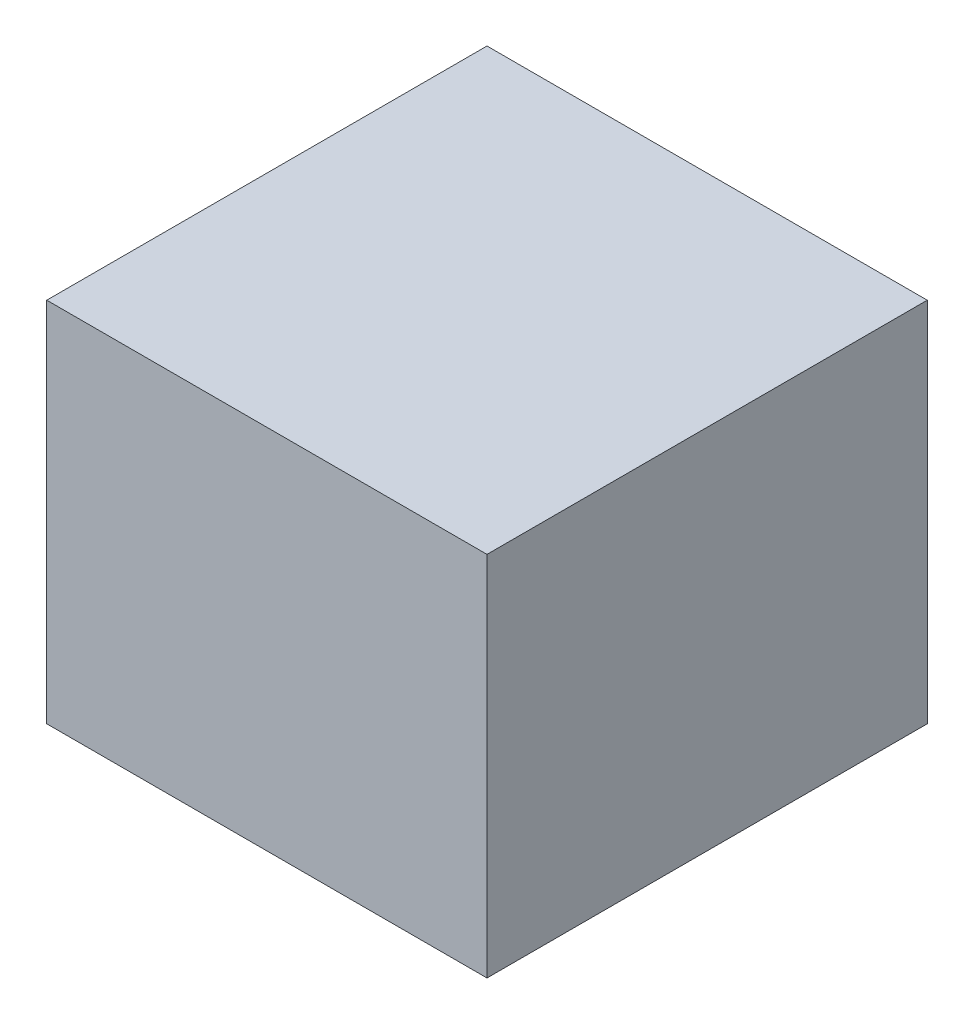
SolidWorks part; units mm, degrees
ref_plane "Front Plane" through (0, 0, 0) normal (0, 0, 1) x (1, 0, 0)
ref_plane "Top Plane" through (0, 0, 0) normal (0, 1, 0) x (1, 0, 0)
ref_plane "Right Plane" through (0, 0, 0) normal (1, 0, 0) x (0, 0, -1)
sketch "Sketch1" plane through (0, 0, 0) normal (0, 0, 1) x (1, 0, 0)
  line L1 (-31.034, 220.9056) -> (268.966, 220.9056)
  line L2 (-31.034, 220.9056) -> (-31.034, -29.0944)
  line L3 (-31.034, -29.0944) -> (268.966, -29.0944)
  line L4 (268.966, 220.9056) -> (268.966, -29.0944)
extrude "Boss-Extrude1" add sketch "Sketch1" along normal blind 300 contours L4 L3 L2 L1
